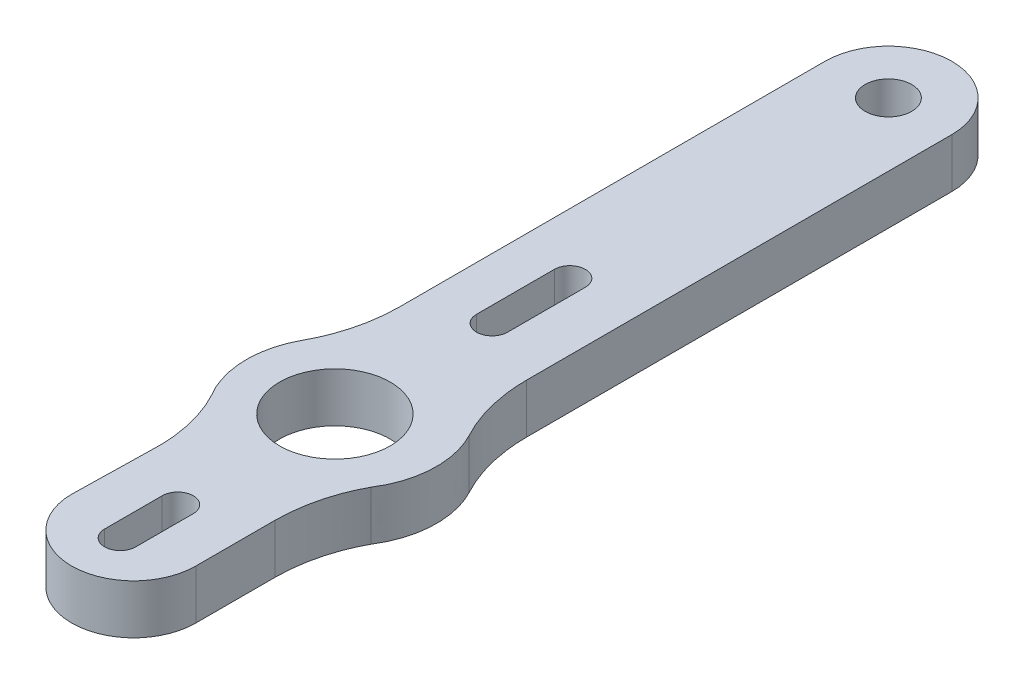
SolidWorks part; units mm, degrees
material "Acrylic (Medium-high impact)"
ref_plane "Front Plane" through (0, 0, 0) normal (0, 0, 1) x (1, 0, 0)
ref_plane "Top Plane" through (0, 0, 0) normal (0, 1, 0) x (1, 0, 0)
ref_plane "Right Plane" through (0, 0, 0) normal (1, 0, 0) x (0, 0, -1)
sketch "Sketch1" plane through (0, 0, 0) normal (0, 1, 0) x (1, 0, 0)
  line L1 (-3.8805, 24.4467) -> (-3.8805, -2.8742)
  line L2 (4.2752, 24.4794) -> (4.2752, -2.8747)
  line L4 (3.994, -18.7597) -> (3.994, -23.8435)
  line L5 (-3.9919, -23.8435) -> (-3.8805, -18.3161)
  line L6 (0.9993, -0.813) -> (0.9993, 4.1872)
  line L7 (-0.9972, 4.1872) -> (-0.9972, -0.813)
  line L8 (0.9993, -24.7137) -> (0.9993, -21.0136)
  line L9 (-0.9972, -24.7137) -> (-0.9972, -21.0136)
  line L11 (-3.9919, -23.8435) -> (3.994, -23.8435) construction
  line L12 (0.001, -7.3632) -> (0.001, -14.4634) construction
  arc A0 (4.2752, 24.4794) -> (-3.8805, 24.4467) centre (0.1973, 24.463) ccw
  arc A1 (3.994, -23.8435) -> (-3.9919, -23.8435) centre (0.0011, -23.8435) cw
  circle A2 centre (0.1973, 24.463) radius 1.4986
  circle A3 centre (0.001, -10.9133) radius 3.556
  arc A4 (-0.9972, -24.7137) -> (0.9993, -24.7137) centre (0.0011, -24.7137) ccw
  arc A5 (-0.9972, -21.0136) -> (0.9993, -21.0136) centre (0.0011, -21.0136) cw
  arc A6 (-0.9972, 4.1872) -> (0.9993, 4.1872) centre (0.0011, 4.1872) cw
  arc A7 (0.9993, -0.813) -> (-0.9972, -0.813) centre (0.0011, -0.813) cw
  spline S2 degree 3 poles (-5.0163, -13.8183) (-6.0956, -12.0231) (-6.1865, -9.7355) (-5.1264, -7.8162) knots 1.005659 1.005659 1.005659 1.005659 2 2 2 2
  spline S3 degree 3 poles (-5.1264, -7.8162) (-4.3086, -6.3339) (-3.8799, -4.5677) (-3.8805, -2.8742) knots 2 2 2 2 3 3 3 3
  spline S7 degree 3 poles (4.2752, -2.8747) (4.2752, -4.5682) (4.7046, -6.3342) (5.5229, -7.8162) knots 8 8 8 8 9 9 9 9
  spline S8 degree 3 poles (5.5229, -7.8162) (6.5299, -9.7664) (6.3739, -12.0533) (5.2418, -13.8183) knots 9 9 9 9 10 10 10 10
  spline S9 degree 3 poles (5.2418, -13.8183) (4.4234, -15.3002) (3.994, -17.0663) (3.994, -18.7597) knots 11 11 11 11 12 12 12 12
  spline S13 degree 3 poles (-3.8805, -18.3161) (-3.8805, -16.7747) (-4.2714, -15.1672) (-5.0163, -13.8183) knots 17 17 17 17 18 18 18 18
  point P6 (0, 0)
  point P53 (0.1973, 24.463)
  dimension "D2" = 2.9972
  dimension "D3" = 7.112
  dimension "D1" = 35.3763
  dimension "D4" = 3.7001
extrude "Boss-Extrude2" add sketch "Sketch1" along normal blind 3.175
